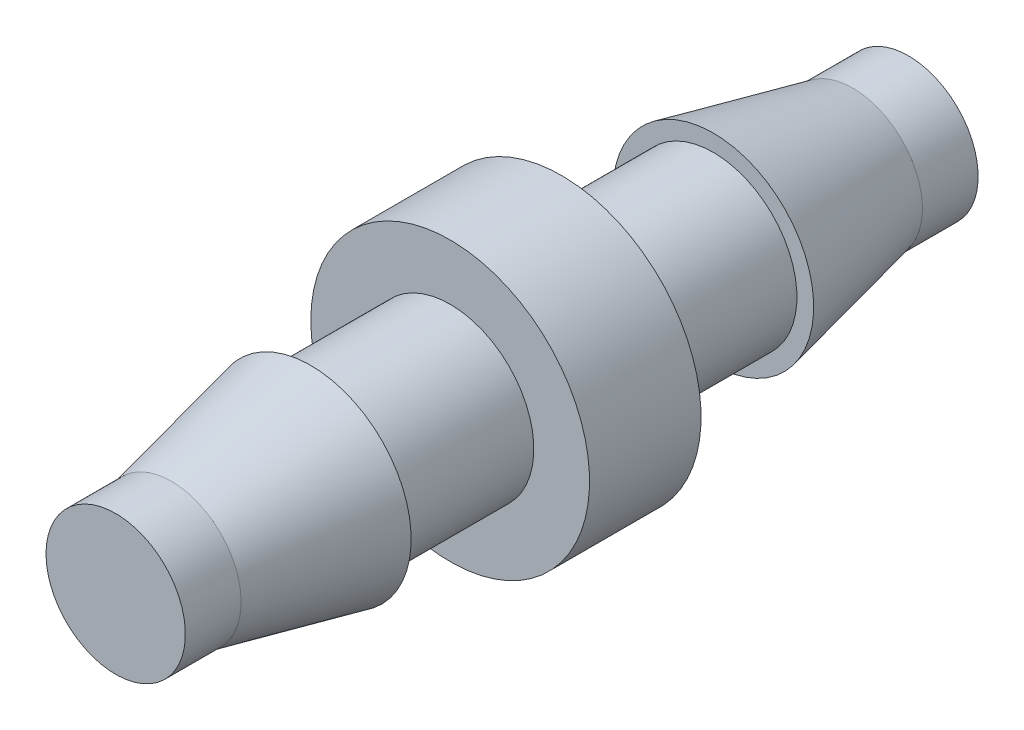
SolidWorks part; units mm, degrees
ref_plane "Front Plane" through (0, 0, 0) normal (0, 0, 1) x (1, 0, 0)
ref_plane "Top Plane" through (0, 0, 0) normal (0, 1, 0) x (1, 0, 0)
ref_plane "Right Plane" through (0, 0, 0) normal (1, 0, 0) x (0, 0, -1)
sketch "Sketch1" plane through (0, 0, 0) normal (1, 0, 0) x (0, 0, -1)
  line L0 (0, 0) -> (0, 3.175)
  line L1 (0, 3.175) -> (2.54, 3.175)
  line L2 (2.54, 3.175) -> (8.89, 4.572)
  line L3 (8.89, 4.572) -> (8.89, 3.81)
  line L4 (8.89, 3.81) -> (15.24, 3.81)
  line L5 (15.24, 3.81) -> (15.24, 6.35)
  line L6 (15.24, 6.35) -> (20.32, 6.35)
  line L7 (20.32, 6.35) -> (20.8788, 3.81)
  line L8 (20.8788, 3.81) -> (27.2288, 3.81)
  line L9 (27.2288, 3.81) -> (27.2288, 4.572)
  line L10 (27.2288, 4.572) -> (33.5788, 3.175)
  line L11 (33.5788, 3.175) -> (36.1188, 3.175)
  line L12 (36.1188, 0) -> (0, 0)
  line L13 (36.1188, 3.175) -> (36.1188, 0)
  dimension "D1" = 3.175
  dimension "D2" = 6.35
  dimension "D3" = 3.81
  dimension "D4" = 0.762
  dimension "D5" = 6.35
  dimension "D6" = 6.35
  dimension "D7" = 2.54
  dimension "D8" = 6.35
  dimension "D9" = 5.08
revolve "Revolve1" add sketch "Sketch1" angle 360 about L12
